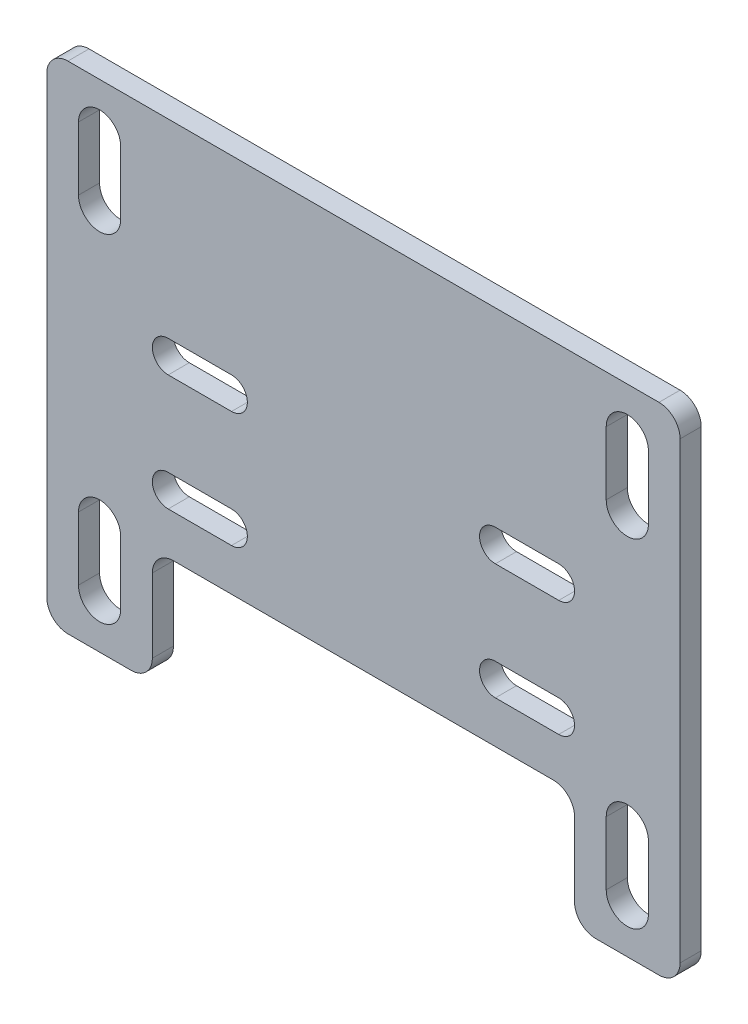
SolidWorks part; units mm, degrees
material "6061 Alloy"
ref_plane "Front" through (0, 0, 0) normal (0, 0, 1) x (1, 0, 0)
ref_plane "Top" through (0, 0, 0) normal (0, 1, 0) x (1, 0, 0)
ref_plane "Right" through (0, 0, 0) normal (1, 0, 0) x (0, 0, -1)
sketch "Sketch1" plane through (0, 0, 0) normal (0, 0, 1) x (1, 0, 0)
  line L1 (-30, 23.5) -> (30, 23.5)
  line L2 (-30, 23.5) -> (-30, -23.5)
  line L3 (-30, -23.5) -> (30, -23.5)
  line L4 (30, 23.5) -> (30, -23.5)
  line L5 (-30, 23.5) -> (30, -23.5) construction
  line L6 (-30, -23.5) -> (30, 23.5) construction
  point P0 (0, 0)
  dimension "D1" = 60
  dimension "D2" = 47
extrude "Boss-Extrude1" add sketch "Sketch1" along normal blind 2
sketch "Sketch2" plane through (0, 0, 0) normal (0, 0, -1) x (-1, 0, 0)
  line L0 (30, -23.5) -> (-30, -23.5) construction
  line L1 (20, -23.5) -> (-20, -23.5)
  line L2 (20, -23.5) -> (20, -12.5)
  line L3 (20, -12.5) -> (-20, -12.5)
  line L4 (-20, -23.5) -> (-20, -12.5)
  line L5 (0, -12.5) -> (0, -23.5) construction
  line L6 (20, -18) -> (-20, -18) construction
  line L7 (-30, -23.5) -> (-30, 23.5) construction
  line L8 (30, 23.5) -> (30, -23.5) construction
  point P284 (0, -18)
  dimension "D1" = 11
  dimension "D2" = 10
  dimension "D3" = 10
extrude "Cut-Extrude1" cut sketch "Sketch2" against normal blind 2
sketch "Sketch3" plane through (0, 0, 0) normal (0, 0, -1) x (-1, 0, 0)
  line L0 (25, -19) -> (25, -13) construction
  line L1 (30, -23.5) -> (20, -23.5) construction
  line L2 (30, 23.5) -> (30, -23.5) construction
  line L3 (25, -13) -> (25, -19) construction
  line L4 (27, -13) -> (27, -19)
  line L5 (23, -13) -> (23, -19)
  arc A0 (27, -13) -> (23, -13) centre (25, -13) ccw
  arc A1 (23, -19) -> (27, -19) centre (25, -19) ccw
  point P6 (25, -16)
  dimension "D1" = 4.5
  dimension "D2" = 5
  dimension "D3" = 6
extrude "Cut-Extrude2" cut sketch "Sketch3" against normal blind 2
sketch "Sketch4" plane through (0, 0, 0) normal (0, 0, -1) x (-1, 0, 0)
  line L0 (25, 19) -> (25, 13) construction
  line L1 (-30, 23.5) -> (30, 23.5) construction
  line L2 (30, 23.5) -> (30, -23.5) construction
  line L3 (25, 19) -> (25, 13) construction
  line L4 (27, 19) -> (27, 13)
  line L5 (23, 19) -> (23, 13)
  arc A0 (27, 19) -> (23, 19) centre (25, 19) ccw
  arc A1 (23, 13) -> (27, 13) centre (25, 13) ccw
  point P6 (25, 16)
  dimension "D1" = 4.5
  dimension "D2" = 6
  dimension "D3" = 5
extrude "Cut-Extrude3" cut sketch "Sketch4" against normal blind 2
sketch "Sketch5" plane through (0, 0, 0) normal (0, 0, -1) x (-1, 0, 0)
  line L0 (12.5, -7) -> (18.5, -7) construction
  line L1 (20, -12.5) -> (-20, -12.5) construction
  line L2 (30, 23.5) -> (30, -23.5) construction
  line L3 (12.5, -7) -> (18.5, -7) construction
  line L4 (12.5, -5.5) -> (18.5, -5.5)
  line L5 (12.5, -8.5) -> (18.5, -8.5)
  arc A0 (12.5, -5.5) -> (12.5, -8.5) centre (12.5, -7) ccw
  arc A1 (18.5, -8.5) -> (18.5, -5.5) centre (18.5, -7) ccw
  point P6 (15.5, -7)
  dimension "D1" = 5.5
  dimension "D2" = 6
  dimension "D3" = 11.5
extrude "Cut-Extrude4" cut sketch "Sketch5" against normal blind 2
sketch "Sketch6" plane through (0, 0, 0) normal (0, 0, -1) x (-1, 0, 0)
  line L0 (12.5, 4) -> (18.5, 4) construction
  line L1 (18.5, -5.5) -> (12.5, -5.5) construction
  line L2 (30, 23.5) -> (30, -23.5) construction
  line L3 (12.5, 4) -> (18.5, 4) construction
  line L4 (12.5, 5.5) -> (18.5, 5.5)
  line L5 (12.5, 2.5) -> (18.5, 2.5)
  arc A0 (12.5, 5.5) -> (12.5, 2.5) centre (12.5, 4) ccw
  arc A1 (18.5, 2.5) -> (18.5, 5.5) centre (18.5, 4) ccw
  point P6 (15.5, 4)
  dimension "D1" = 9.5
  dimension "D2" = 6
  dimension "D3" = 11.5
extrude "Cut-Extrude5" cut sketch "Sketch6" against normal blind 2
ref_plane "Plane3" through (0, 0, 0) normal (-1, 0, 0) x (0, 0, 1)
mirror "Mirror1" about plane through (0, 0, 0) normal (-1, 0, 0) of "Cut-Extrude2", "Cut-Extrude4", "Cut-Extrude3", "Cut-Extrude5"
fillet "Fillet1" radius 2 8 edges at (30, 23.5, 1) (-30, 23.5, 1) (-30, -23.5, 1) (20, -12.5, 1) (30, -23.5, 1) (20, -23.5, 1) (-20, -12.5, 1) (-20, -23.5, 1)
